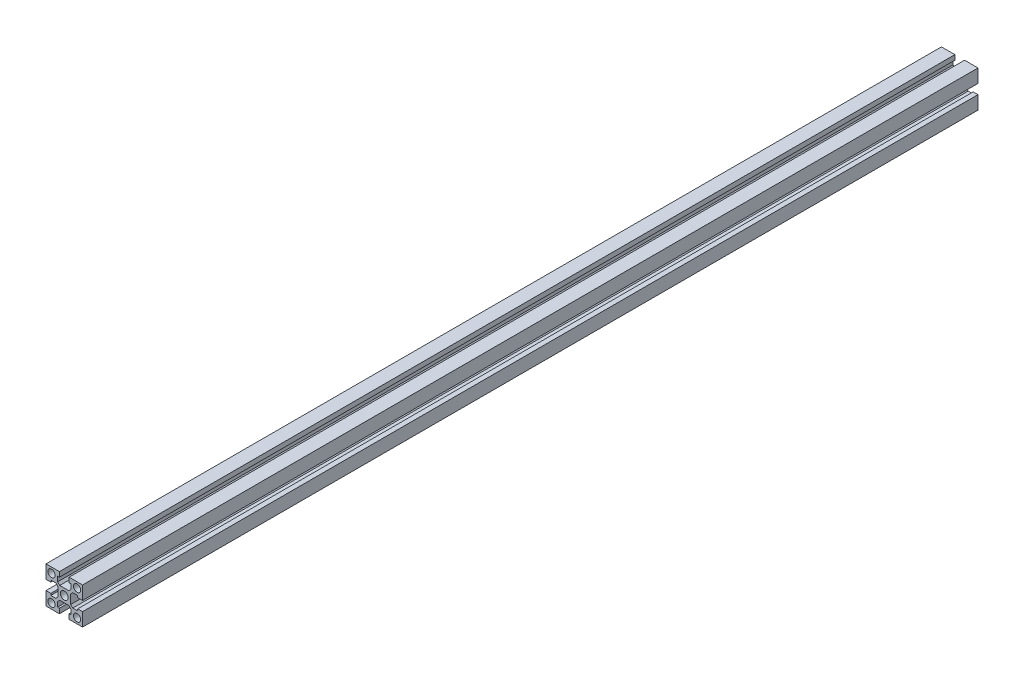
SolidWorks part; units mm, degrees
ref_plane "정면" through (0, 0, 0) normal (0, 0, 1) x (1, 0, 0)
ref_plane "윗면" through (0, 0, 0) normal (0, 1, 0) x (1, 0, 0)
ref_plane "우측면" through (0, 0, 0) normal (1, 0, 0) x (0, 0, -1)
sketch "스케치1" plane through (0, 0, 0) normal (0, 0, 1) x (1, 0, 0)
  line L0 (-10, -10) -> (-2.65, -10)
  line L1 (2.65, -10) -> (10, -10)
  line L2 (10, -10) -> (10, -2.65)
  line L3 (10, 2.65) -> (10, 10)
  line L4 (10, 10) -> (2.65, 10)
  line L5 (-2.65, 10) -> (-10, 10)
  line L6 (-10, 10) -> (-10, 2.65)
  line L7 (-10, -2.65) -> (-10, -10)
  line L8 (0, 10) -> (0, -10) construction
  line L9 (-10, 0) -> (10, 0) construction
  line L10 (2.65, 10) -> (2.65, 7.35)
  line L11 (-2.65, 10) -> (-2.65, 7.35)
  line L12 (-2.5101, 3.5) -> (0, 3.5)
  line L13 (-2.65, 7.35) -> (-3.65, 7.35)
  line L14 (-3.65, 7.35) -> (-3.65, 4.6399)
  line L15 (2.65, 7.35) -> (3.65, 7.35)
  line L16 (2.65, -10) -> (2.65, -7.35)
  line L17 (-2.65, -10) -> (-2.65, -7.35)
  line L18 (0, -3.5) -> (2.5101, -3.5)
  line L19 (-2.65, -7.35) -> (-3.65, -7.35)
  line L20 (2.65, -7.35) -> (3.65, -7.35)
  line L21 (3.65, -7.35) -> (3.65, -4.6399)
  line L22 (-10, 2.65) -> (-7.35, 2.65)
  line L23 (-10, -2.65) -> (-7.35, -2.65)
  line L24 (-3.5, 0) -> (-3.5, 2.5101)
  line L25 (-7.35, -2.65) -> (-7.35, -3.65)
  line L26 (-7.35, 2.65) -> (-7.35, 3.65)
  line L27 (-7.35, 3.65) -> (-4.6399, 3.65)
  line L28 (10, 2.65) -> (7.35, 2.65)
  line L29 (10, -2.65) -> (7.35, -2.65)
  line L30 (3.5, -2.5101) -> (3.5, 0)
  line L31 (7.35, -2.65) -> (7.35, -3.65)
  line L32 (7.35, -3.65) -> (4.6399, -3.65)
  line L33 (7.35, 2.65) -> (7.35, 3.65)
  line L34 (2.5101, -3.5) -> (3.65, -4.6399)
  line L35 (-4.6399, 3.65) -> (-3.5, 2.5101)
  line L36 (-3.65, 4.6399) -> (-2.5101, 3.5)
  line L37 (3.5, -2.5101) -> (4.6399, -3.65)
  line L38 (-2.5101, -3.5) -> (0, -3.5)
  line L39 (-2.65, -7.35) -> (-3.65, -7.35)
  line L40 (-3.65, -7.35) -> (-3.65, -4.6399)
  line L41 (0, 3.5) -> (2.5101, 3.5)
  line L42 (2.65, 7.35) -> (3.65, 7.35)
  line L43 (3.65, 7.35) -> (3.65, 4.6399)
  line L44 (-3.5, 0) -> (-3.5, -2.5101)
  line L45 (-7.35, -2.65) -> (-7.35, -3.65)
  line L46 (-7.35, -3.65) -> (-4.6399, -3.65)
  line L47 (3.5, 2.5101) -> (3.5, 0)
  line L48 (7.35, 2.65) -> (7.35, 3.65)
  line L49 (7.35, 3.65) -> (4.6399, 3.65)
  line L50 (2.5101, 3.5) -> (3.65, 4.6399)
  line L51 (-4.6399, -3.65) -> (-3.5, -2.5101)
  line L52 (-3.65, -4.6399) -> (-2.5101, -3.5)
  line L53 (3.5, 2.5101) -> (4.6399, 3.65)
  circle A0 centre (-7, 7) radius 2
  circle A1 centre (0, 0) radius 2.15
  circle A2 centre (7, 7) radius 2
  circle A3 centre (-7, -7) radius 2
  circle A4 centre (7, -7) radius 2
extrude "보스-돌출1" add sketch "스케치1" along normal mid plane 490 contours L47 L53 L49 L33 L28 L3 L4 L10 L15 L43 L50 L41 L12 L36 L14 L13 L11 L5 L6 L22 L26 L27 L35 L24 L44 L51 L46 L25 L23 L7 L0 L17 L19 L40 L52 L38 L18 L34 L21 L20 L16 L1 L2 L29 L31 L32 L37 L30 A4
